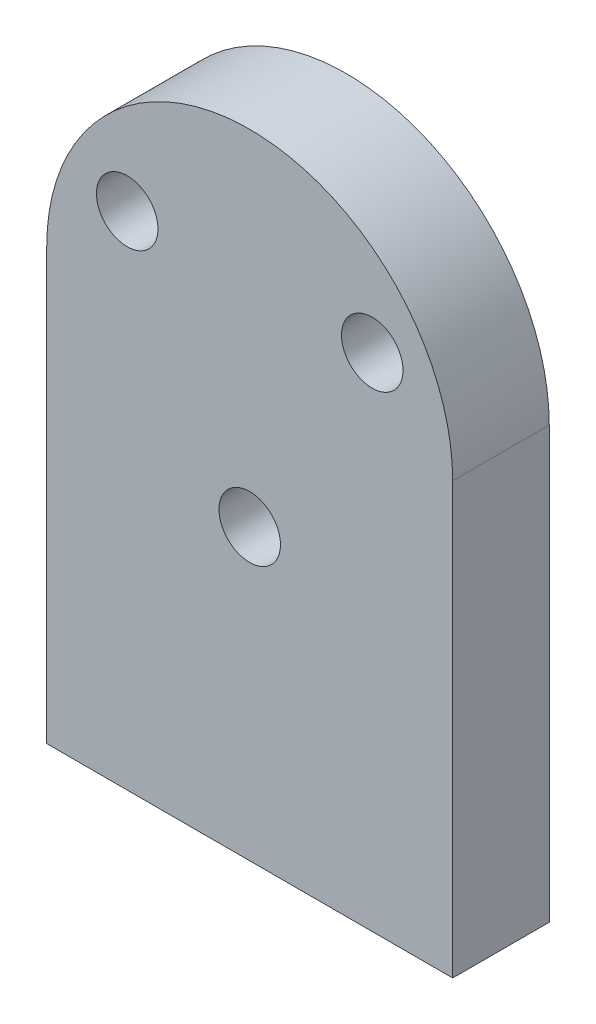
SolidWorks part; units mm, degrees
ref_plane "Front Plane" through (0, 0, 0) normal (0, 0, 1) x (1, 0, 0)
ref_plane "Top Plane" through (0, 0, 0) normal (0, 1, 0) x (1, 0, 0)
ref_plane "Right Plane" through (0, 0, 0) normal (1, 0, 0) x (0, 0, -1)
sketch "Sketch1" plane through (0, 0, 0) normal (0, 0, 1) x (1, 0, 0)
  line L0 (3.3, 0) -> (3.3, -7)
  line L1 (3.3, -7) -> (-3.3, -7)
  line L2 (-3.3, -7) -> (-3.3, 0)
  arc A0 (3.3, 0) -> (-3.3, 0) centre (0, 0) ccw
  circle A1 centre (0, -2.3) radius 0.5
  circle A2 centre (-1.9919, 1.15) radius 0.5
  circle A3 centre (1.9919, 1.15) radius 0.5
  point P14 (0, 0)
  dimension "D1" = 6.6
  dimension "D4" = 1
  dimension "D2" = 7
  dimension "D3" = 2.3
  dimension "D5" = 3
extrude "Boss-Extrude1" add sketch "Sketch1" along normal blind 1.57
